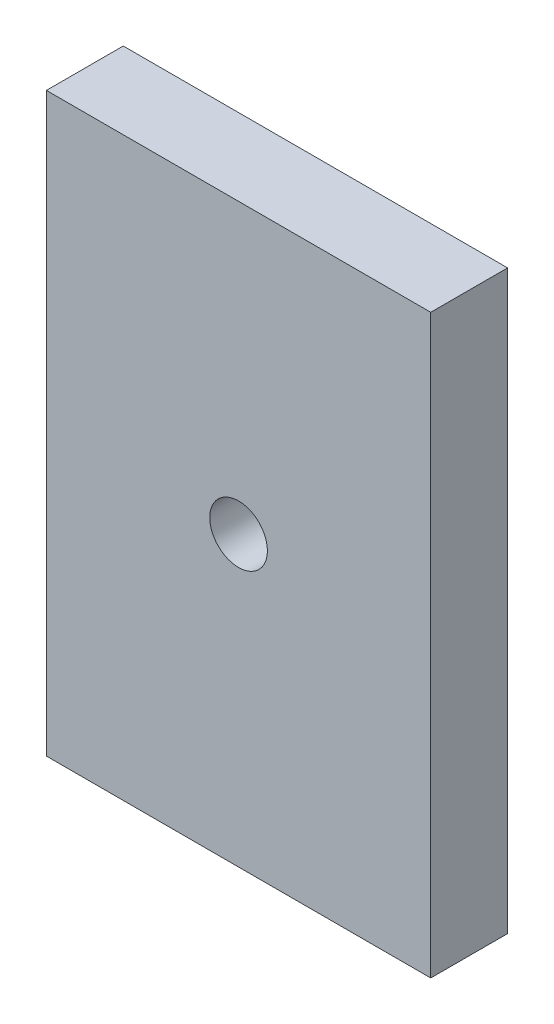
SolidWorks part; units mm, degrees
material "Mahogany"
ref_plane "Front Plane" through (0, 0, 0) normal (0, 0, 1) x (1, 0, 0)
ref_plane "Top Plane" through (0, 0, 0) normal (0, 1, 0) x (1, 0, 0)
ref_plane "Right Plane" through (0, 0, 0) normal (1, 0, 0) x (0, 0, -1)
sketch "Sketch1" plane through (0, 0, 0) normal (0, 0, 1) x (1, 0, 0)
  line L1 (-10, -15) -> (10, -15)
  line L2 (-10, -15) -> (-10, 15)
  line L3 (-10, 15) -> (10, 15)
  line L4 (10, -15) -> (10, 15)
  line L5 (-10, -15) -> (10, 15) construction
  line L6 (-10, 15) -> (10, -15) construction
  point P0 (0, 0)
  dimension "D1" = 20
  dimension "D2" = 30
extrude "Boss-Extrude1" add sketch "Sketch1" along normal blind 4
sketch "Sketch2" plane through (0, 0, 4) normal (0, 0, 1) x (1, 0, 0)
  line L0 (-10, -15) -> (10, -15) construction
  line L1 (-10, 15) -> (-10, -15) construction
  circle A0 centre (0, 0) radius 1.5
  dimension "D1" = 3
  dimension "D2" = 15
  dimension "D3" = 10
extrude "Cut-Extrude1" cut sketch "Sketch2" against normal through all
